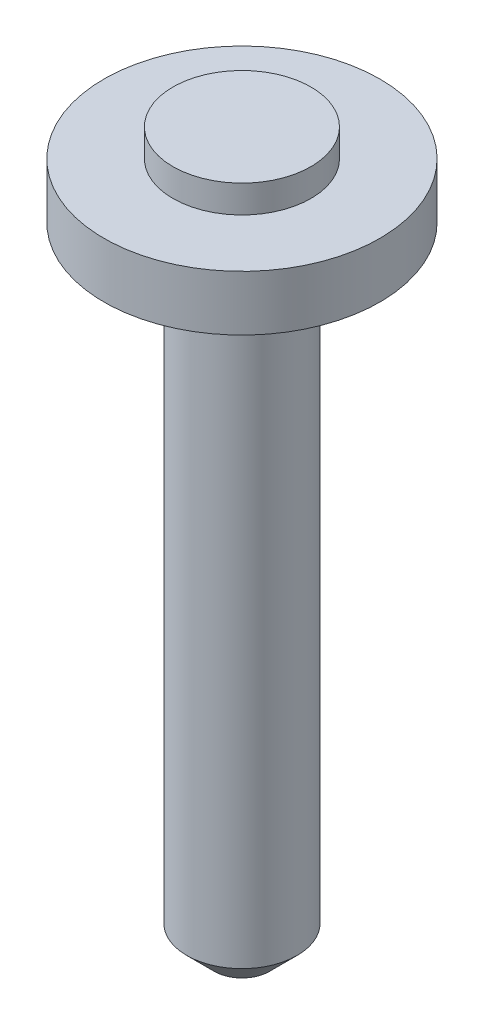
SolidWorks part; units mm, degrees
ref_plane "Front Plane" through (0, 0, 0) normal (0, 0, 1) x (1, 0, 0)
ref_plane "Top Plane" through (0, 0, 0) normal (0, 1, 0) x (1, 0, 0)
ref_plane "Right Plane" through (0, 0, 0) normal (1, 0, 0) x (0, 0, -1)
sketch "Sketch1" plane through (0, 0, 0) normal (0, 0, 1) x (1, 0, 0)
  line L0 (0, 0) -> (0, 9.0055) construction
  line L1 (0, 25) -> (-5, 25)
  line L2 (-5, 25) -> (-5, 23)
  line L3 (-5, 23) -> (-2.5, 23)
  line L4 (-2.5, 23) -> (-2.5, 22)
  line L5 (-2.5, 22) -> (-2, 22)
  line L6 (-2, 22) -> (-2, 0)
  line L7 (-2, 0) -> (-0.45, 0)
  line L8 (-0.45, 0) -> (-0.45, 19)
  line L9 (-0.45, 19) -> (0, 19)
  line L10 (0, 25) -> (0, 19)
  dimension "D1" = 10
  dimension "D2" = 2
  dimension "D3" = 5
  dimension "D4" = 1
  dimension "D5" = 25
  dimension "D6" = 4
  dimension "D7" = 0.9
  dimension "D8" = 19
revolve "Revolve1" add sketch "Sketch1" angle 360 about L0
chamfer "Chamfer1" distance 1 angle 45 1 edges at (0, 0, -2)
sketch "Sketch2" plane through (0, 25, 0) normal (0, 1, 0) x (1, 0, 0)
  circle A0 centre (0, 0) radius 2.5 construction
  circle A1 centre (0, 0) radius 2.5
extrude "Boss-Extrude1" add sketch "Sketch2" along normal blind 1
